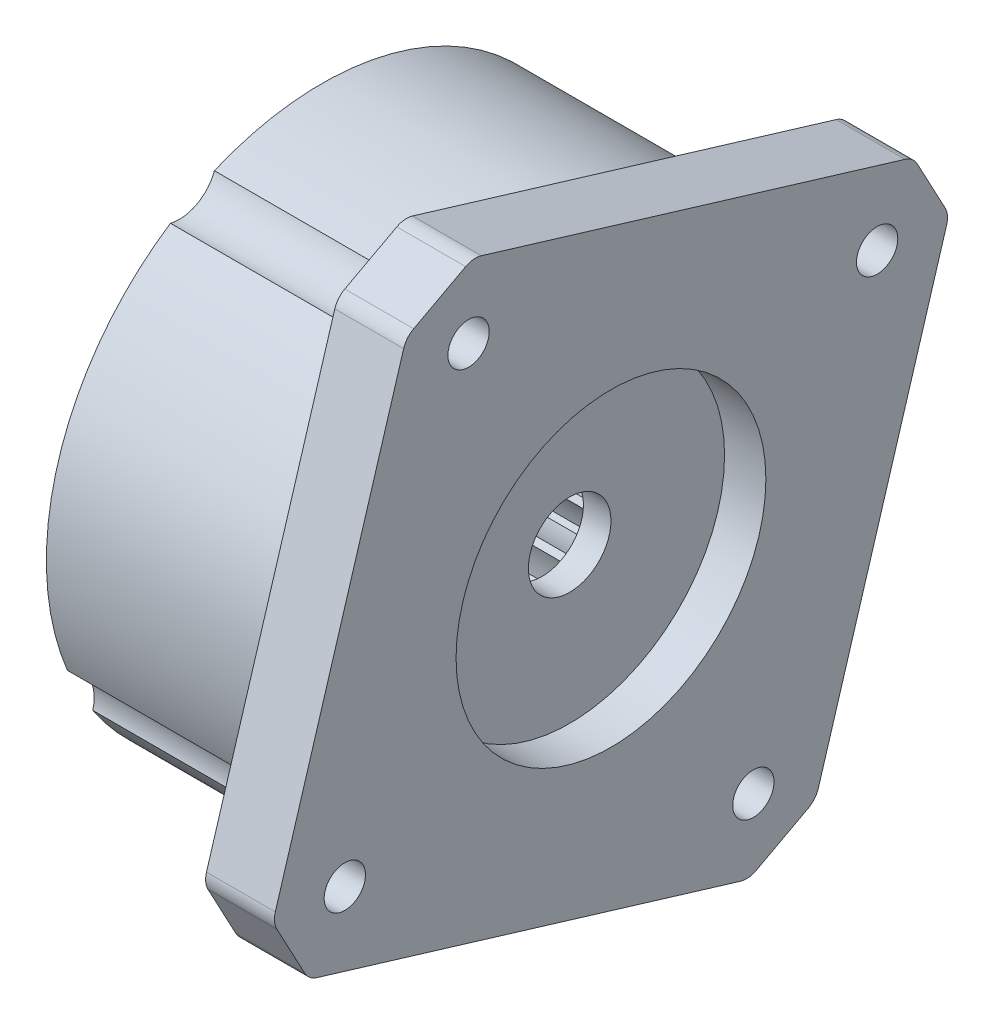
SolidWorks part; units mm, degrees
ref_plane "Plane1" through (0, 0, 0) normal (0, 0, 1) x (1, 0, 0)
ref_plane "Plane2" through (0, 0, 0) normal (0, 1, 0) x (1, 0, 0)
ref_plane "Plane3" through (0, 0, 0) normal (1, 0, 0) x (0, 0, -1)
sketch "HoldingSke" plane through (0, 0, 0) normal (0, 1, 0) x (1, 0, 0)
  line L0 (0, 0) -> (0.866, -0.5)
  line L1 (-15, 0) -> (100, 0) construction
  line L2 (0, 0) -> (-2.1039, 2.3779)
  line L3 (0, 0) -> (-11.863, 4.5341)
  line L4 (0, 0) -> (7.479, 4.318)
  line L5 (0, 0) -> (-23.7986, -8.8762)
  line L6 (0, 0) -> (-10.5278, -7.1032)
  line L7 (-2.1039, 2.3779) -> (3.3635, 27.1825)
  line L8 (-76.2, 3.3779) -> (-54.61, 3.3779)
  line L9 (-71.009, 38.7566) -> (-53.1078, 45.2721)
  line L10 (-76.2, 71.12) -> (104.1128, 71.12)
  line L11 (0, 0) -> (-16, 0)
  line L12 (-76.2, 101.6) -> (-76.162, 101.6)
  line L13 (24.9733, 27.94) -> (52.9518, 28.4284)
  line L14 (24.9733, 27.94) -> (24.9743, 27.94)
  line L15 (24.9733, 27.94) -> (100.4006, 29.5858)
  circle A0 centre (0, 0) radius 20
  circle A1 centre (0, 0) radius 12.7
  circle A2 centre (0, 0) radius 12.7
  dimension "MHD" = 25.4
  dimension "Hub_dia" = 25.4
  dimension "Diameter" = 40
  dimension "Num_teeth" = 30
  dimension "Pitch" = 1
  dimension "Overall_len" = 25.4
  dimension "Show_teeth" = 30
  dimension "Thickness" = 12.7
  dimension "OAL" = 25.4001
  dimension "T_dim" = 21.59
  dimension "Ap" = 20
  dimension "H" = 19.05
  dimension "Pitch_radius" = 180.3128
  dimension "Width" = 16
  dimension "Backlash" = 0.038
  dimension "Addendum_fac" = 1
  dimension "Dedendum_fac" = 1.25
  dimension "Clearance_fac" = 0.25
  dimension "Dedendum_add" = 0.001
  dimension "Module" = 1
sketch "BasProSke" plane through (0, 0, 0) normal (0, 1, 0) x (1, 0, 0)
  line L0 (-10, 0) -> (60, 0) construction
  line L1 (0, 14) -> (0, 20)
  line L2 (0, 14) -> (16, 14)
  line L3 (16, 14) -> (16, 20)
  line L4 (16, 20) -> (0, 20)
  dimension "Diameter" = 40
  dimension "Thickness" = 16
  dimension "Inside_diameter" = 28
revolve "Base-Revolve" add sketch "BasProSke" angle 360 about L0
sketch "TooCutSke" plane through (0, 0, 0) normal (1, 0, 0) x (0, 0, -1)
  line L3 (0.88, 14.9742) -> (0.88, 53.6633) construction
  line L4 (0, 0) -> (0, 59.563) construction
  line L5 (0, 0) -> (-7.1422, 67.9532) construction
  line L6 (-6.0554, 12.1193) -> (36.3095, 16.572) construction
  circle A0 centre (0, 0) radius 15 construction
  circle A1 centre (0, 0) radius 16.251 construction
  circle A2 centre (0, 0) radius 12.6859 construction
  circle A3 centre (0, 0) radius 13.9746 construction
  arc A4 (1.2251, 13.9208) -> (0.2048, 16.2497) centre (-6.0554, 12.1193) ccw
  arc A5 (1.2251, 13.9208) -> (-1.2251, 13.9208) centre (0, 0) ccw
  arc A6 (0.2048, 16.2497) -> (-0.2048, 16.2497) centre (0, 0) ccw
  arc A7 (-0.2048, 16.2497) -> (-1.2251, 13.9208) centre (6.0554, 12.1193) ccw
  dimension "Pitch_dia" = 30
  dimension "Base_dia" = 25.3717
  dimension "Root_dia" = 32.502
  dimension "Overcut_dia" = 27.9492
  dimension "Flank_rad" = 7.5
  dimension "Half_ang" = 6
  dimension "Half_CT" = 0.88
extrude "ToothCut" cut sketch "TooCutSke" along normal through all
fillet "Breaks" [suppressed] radius 0.1
fillet "RootFillets" [suppressed] radius 0.251
pattern_circular "TeethCuts" count 30 every 12 about axis through (-10, 0, 0) along (1, 0, 0) of "RootFillets", "Breaks", "ToothCut"
sketch "Sketch1" plane through (16, 0, 0) normal (1, 0, 0) x (0, 0, -1)
  line L16 (-24.2617, -10.5516) -> (-22.2413, -14.328)
  line L17 (-21.3535, -15.056) -> (9.4092, -24.3746)
  line L18 (10.5516, -24.2617) -> (14.328, -22.2413)
  line L19 (15.056, -21.3535) -> (24.3746, 9.4092)
  line L20 (24.2617, 10.5516) -> (22.2413, 14.328)
  line L21 (21.3535, 15.056) -> (-9.4092, 24.3746)
  line L22 (-10.5516, 24.2617) -> (-14.328, 22.2413)
  line L23 (-15.056, 21.3535) -> (-24.3746, -9.4092)
  line L25 (-16.4393, 16.7869) -> (-22.9913, -4.8425)
  line L28 (16.7869, 16.4393) -> (-4.8425, 22.9913)
  line L31 (16.4393, -16.7869) -> (22.9913, 4.8425)
  line L34 (-16.7869, -16.4393) -> (4.8425, -22.9913)
  circle A2 centre (19.328, 10.3407) radius 1.5
  circle A4 centre (-10.3407, 19.328) radius 1.5
  circle A6 centre (-19.328, -10.3407) radius 1.5
  circle A8 centre (10.3407, -19.328) radius 1.5
  circle A13 centre (0, 0) radius 3
  arc A24 (-22.2413, -14.328) -> (-21.3535, -15.056) centre (-20.9187, -13.6204) ccw
  arc A25 (9.4092, -24.3746) -> (10.5516, -24.2617) centre (9.844, -22.9391) ccw
  arc A26 (14.328, -22.2413) -> (15.056, -21.3535) centre (13.6204, -20.9187) ccw
  arc A27 (24.3746, 9.4092) -> (24.2617, 10.5516) centre (22.9391, 9.844) ccw
  arc A28 (22.2413, 14.328) -> (21.3535, 15.056) centre (20.9187, 13.6204) ccw
  arc A29 (-9.4092, 24.3746) -> (-10.5516, 24.2617) centre (-9.844, 22.9391) ccw
  arc A30 (-14.328, 22.2413) -> (-15.056, 21.3535) centre (-13.6204, 20.9187) ccw
  arc A31 (-24.3746, -9.4092) -> (-24.2617, -10.5516) centre (-22.9391, -9.844) ccw
extrude "Boss-Extrude2" add sketch "Sketch1" along normal blind 5 contours L23 A31 L16 A24 L17 A25 L18 A26 L19 A27 L20 A28 L21 A29 L22 A30 A2 A4 A6 A8 A13
sketch "Sketch2" plane through (21, 0, 0) normal (1, 0, 0) x (0, 0, -1)
  circle A0 centre (0, 0) radius 11.25
extrude "Cut-Extrude1" cut sketch "Sketch2" against normal blind 3
sketch "Sketch3" plane through (16, 0, 0) normal (-1, 0, 0) x (0, 0, 1)
  circle A0 centre (10.3407, 19.328) radius 2.7
  circle A1 centre (19.328, -10.3407) radius 2.8
  circle A2 centre (-10.3407, -19.328) radius 2.8
  circle A3 centre (-19.328, 10.3407) radius 2.8
extrude "Cut-Extrude2" cut sketch "Sketch3" along normal through all
fillet "Fillet1" radius 0.5 4 edges at (16, -19.1411, 5.7982) (16, 5.8622, 19.1216) (16, 19.1603, -5.7343) (16, -5.7982, -19.1411)
equation "' \"Module@HoldingSke\" = 6.35"
equation "' \"Num_teeth@HoldingSke\" = 24"
equation "' \"Ap@HoldingSke\" =  14.5"
equation "' \"Ap@HoldingSke\" = 14.5"
equation "' \"Width@HoldingSke\" = 12"
equation "' \"Diameter@HoldingSke\" = 8 * 25.4"
equation "' \"Show_teeth@HoldingSke\" = 100"
equation "' \"Backlash@HoldingSke\" = 0.009 * 25.4"
equation "' \"Addendum_fac@HoldingSke\" = 1.0"
equation "' \"Dedendum_fac@HoldingSke\" = 1.25"
equation "' \"Dedendum_add@HoldingSke\" = 0.00005 * 25.4"
equation "' \"Clearance_fac@HoldingSke\" = 0.25"
equation "\"Pitch@HoldingSke\" = 1 / \"Module@HoldingSke\" "
equation "\"Overcut_dia@TooCutSke\" = (\"Num_teeth@HoldingSke\" - 2 * \"Addendum_fac@HoldingSke\") / \"Pitch@HoldingSke\" - 0.002 * 25.4"
equation "\"Pitch_dia@TooCutSke\" = \"Num_teeth@HoldingSke\" / \"Pitch@HoldingSke\""
equation "\"Base_dia@TooCutSke\" = \"Num_teeth@HoldingSke\" / \"Pitch@HoldingSke\" * cos((\"Ap@HoldingSke\"  * 3.14159265 / 180)) * 0.90"
equation "\"Root_dia@TooCutSke\" = \"Num_teeth@HoldingSke\"  / \"Pitch@HoldingSke\" + 2 *  \"Dedendum_fac@HoldingSke\"/ \"Pitch@HoldingSke\" + \"Dedendum_add@HoldingSke\" * 2"
equation "\"Half_ang@TooCutSke\" = 180 / \"Num_teeth@HoldingSke\""
equation "\"Half_CT@TooCutSke\" = \"Num_teeth@HoldingSke\" / \"Pitch@HoldingSke\" * sin((3.14159265 / 2 / \"Num_teeth@HoldingSke\")) / 2 + 10 * \"Backlash@HoldingSke\" / 4"
equation "\"Flank_rad@TooCutSke\" = \"Num_teeth@HoldingSke\" / \"Pitch@HoldingSke\" / 4"
equation "\"Radius@RootFillets\"= \"Clearance_fac@HoldingSke\" / \"Pitch@HoldingSke\" + \"Dedendum_add@HoldingSke\""
equation "\"Break_rad@Breaks\" = 0.02 / \"Pitch@HoldingSke\" * 5"
equation "\"Num_teeth@TeethCuts\" = int( \"Show_teeth@HoldingSke\" ) + 1"
equation "\"Num_teeth@TeethCuts\" = ((sgn( \"Num_teeth@TeethCuts\" - \"Num_teeth@HoldingSke\" )-1)*( \"Num_teeth@TeethCuts\" - \"Num_teeth@HoldingSke\" ))/-2+ \"Num_teeth@HoldingSke\""
equation "\"Num_teeth@TeethCuts\" = ((sgn( \"Num_teeth@TeethCuts\" - 2.0)+1)*( \"Num_teeth@TeethCuts\" - 2.0))/2 +2.0"
equation "\"Angle@TeethCuts\" = 360.0 / \"Num_teeth@HoldingSke\""
equation "\"Diameter@BasProSke\" = \"Num_teeth@HoldingSke\"  / \"Pitch@HoldingSke\" + 2 *  \"Dedendum_fac@HoldingSke\"/ \"Pitch@HoldingSke\" + \"Dedendum_add@HoldingSke\" * 2 + 0.002 * 25.4"
equation "\"Diameter@BasProSke\" = ((sgn( \"Diameter@BasProSke\"  - \"Diameter@HoldingSke\" )+1)*( \"Diameter@BasProSke\"  - \"Diameter@HoldingSke\" ))/2 + \"Diameter@HoldingSke\""
equation "\"Inside_diameter@BasProSke\" =  (\"Num_teeth@HoldingSke\" - 2 * \"Addendum_fac@HoldingSke\") / \"Pitch@HoldingSke\" "
equation "\"Thickness@BasProSke\"  = \"Width@HoldingSke\""
